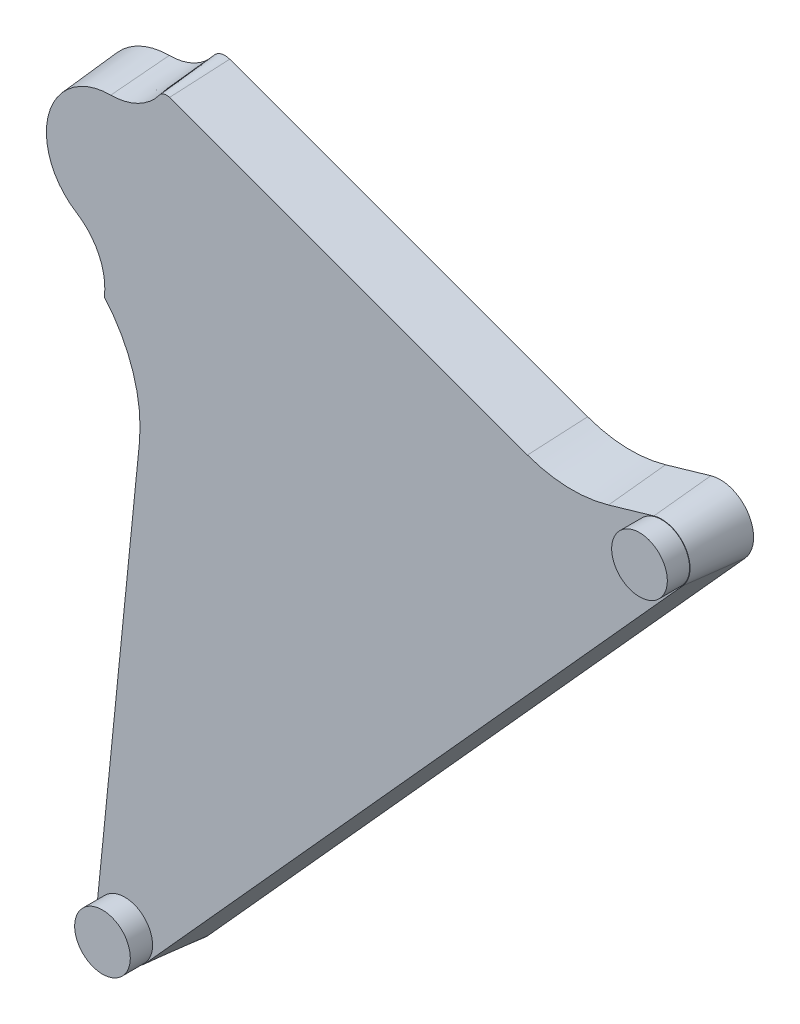
SolidWorks part; units mm, degrees
ref_plane "Спереди" through (0, 0, 0) normal (0, 0, 1) x (1, 0, 0)
ref_plane "Сверху" through (0, 0, 0) normal (0, 1, 0) x (1, 0, 0)
ref_plane "Справа" through (0, 0, 0) normal (1, 0, 0) x (0, 0, -1)
sketch "Эскиз1" plane through (0, 0, 0) normal (0, 0, 1) x (1, 0, 0)
  line L0 (0, 0) -> (0, -279.4414) construction
  line L1 (0, 0) -> (220.368, 0) construction
  line L2 (206.9028, -28.0377) -> (13.9104, -241.9843)
  line L3 (194.6432, -8.4769) -> (178.3526, -13.2118)
  line L4 (150.3602, -12.2709) -> (21.7148, 34.6968)
  line L5 (0, 0) -> (0, 112.2854) construction
  line L6 (-6.9398, -232.7466) -> (8.4118, -80)
  arc A0 (0, 25) -> (-13.3333, -21.1476) centre (0, 0) ccw
  arc A1 (-6.9398, -232.7466) -> (13.9104, -241.9843) centre (5, -233.9466) ccw
  arc A2 (206.9028, -28.0377) -> (194.6432, -8.4769) centre (197.9924, -20) ccw
  arc A3 (178.3526, -13.2118) -> (150.3602, -12.2709) centre (165.793, 30) cw
  arc A4 (0, 25) -> (16, 33) centre (0, 45) ccw
  arc A5 (21.7148, 34.6968) -> (16, 33) centre (20, 30) ccw
  arc A6 (8.4118, -80) -> (-4.2846, -41.428) centre (-41.3376, -75) ccw
  arc A7 (-4.2846, -41.428) -> (-13.3333, -21.1476) centre (-24, -38.0657) ccw
  dimension "D1" = 5
  dimension "D3" = 20
  dimension "D5" = 45
  dimension "D7" = 30
  dimension "D8" = 80
  dimension "D9" = 24
  dimension "D10" = 75
  dimension "D2" = 234
  dimension "D4" = 199
  dimension "D6" = 50
extrude "Бобышка-Вытянуть1" add sketch "Эскиз1" along normal blind 21 draft 5
sketch "Эскиз2" plane through (0, 0, 21) normal (0, 0, 1) x (1, 0, 0)
  circle A0 centre (5, -233.9466) radius 10
  circle A1 centre (197.9924, -20) radius 10
  arc A2 (-5.1118, -232.9303) -> (12.5462, -240.7537) centre (5, -233.9466) ccw construction
  arc A3 (205.5386, -26.8071) -> (195.156, -10.2411) centre (197.9924, -20) ccw construction
extrude "Бобышка-Вытянуть2" add sketch "Эскиз2" along normal blind 8
sketch "Эскиз3" plane through (0, 0, 0) normal (0, 0, -1) x (-1, 0, 0)
  line L0 (-13.9104, -241.9843) -> (-206.9028, -28.0377) construction
  line L1 (-183.6853, -53.7761) -> (-171.4253, -14.6461)
  line L4 (-197.9924, -20) -> (-172.4599, 5.5326) construction
  line L5 (-197.9924, -20) -> (-224.7525, -46.76) construction
  circle A0 centre (-197.9924, -20) radius 12
  arc A1 (-194.6432, -8.4769) -> (-206.9028, -28.0377) centre (-197.9924, -20) ccw construction
  arc A2 (-178.3526, -13.2118) -> (-150.3602, -12.2709) centre (-165.793, 30) ccw construction
  point P9 (-171.4253, -14.6461)
  point P11 (-183.6853, -53.7761)
  dimension "D1" = 15
  dimension "D2" = 34
